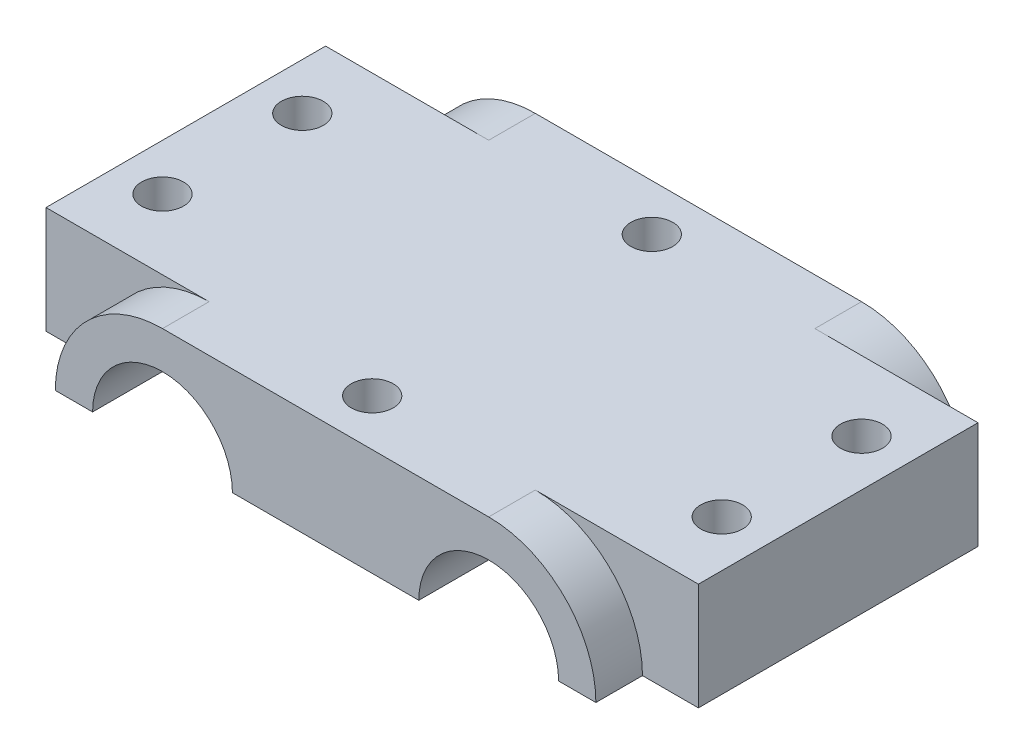
SolidWorks part; units mm, degrees
ref_plane "Front Plane" through (0, 0, 0) normal (0, 0, 1) x (1, 0, 0)
ref_plane "Top Plane" through (0, 0, 0) normal (0, 1, 0) x (1, 0, 0)
ref_plane "Right Plane" through (0, 0, 0) normal (1, 0, 0) x (0, 0, -1)
sketch "Sketch1" plane through (0, 0, 0) normal (0, 0, 1) x (1, 0, 0)
  line L1 (-35, 5.75) -> (35, 5.75)
  line L2 (-35, 5.75) -> (-35, -5.75)
  line L3 (-35, -5.75) -> (35, -5.75)
  line L4 (35, 5.75) -> (35, -5.75)
  line L5 (-35, 5.75) -> (35, -5.75) construction
  line L6 (-35, -5.75) -> (35, 5.75) construction
  point P0 (0, 0)
  dimension "D1" = 11.5
  dimension "D2" = 70
extrude "Boss-Extrude1" add sketch "Sketch1" along normal mid plane 40
sketch "Sketch2" plane through (0, 0, 20) normal (0, 0, 1) x (1, 0, 0)
  line L0 (-35, -5.75) -> (35, -5.75) construction
  line L1 (0, 0) -> (0, 14.1987) construction
  line L2 (-25, -5.75) -> (-10, -5.75)
  line L3 (10, -5.75) -> (25, -5.75)
  arc A0 (-25, -5.75) -> (-10, -5.75) centre (-17.5, -5.75) cw
  arc A1 (10, -5.75) -> (25, -5.75) centre (17.5, -5.75) cw
  dimension "D2" = 7.5
  dimension "D1" = 35
extrude "Cut-Extrude1" cut sketch "Sketch2" against normal through all
sketch "Sketch3" plane through (0, 0, 20) normal (0, 0, 1) x (1, 0, 0)
  line L0 (25, -5.75) -> (35, -5.75) construction
  line L1 (35, 5.75) -> (-35, 5.75) construction
  line L2 (-35, 5.75) -> (-35, -5.75) construction
  line L3 (35, -5.75) -> (35, 5.75) construction
  line L4 (-35, 5.75) -> (-35, -5.75)
  line L5 (35, -5.75) -> (35, 5.75)
  line L6 (35, 5.75) -> (17.5, 5.75)
  line L7 (0, -10.9718) -> (0, 10.9718) construction
  line L8 (-17.5, 5.75) -> (-35, 5.75)
  line L9 (-35, -5.75) -> (-25, -5.75) construction
  line L10 (-35, -5.75) -> (-29, -5.75)
  line L11 (29, -5.75) -> (35, -5.75)
  arc A0 (29, -5.75) -> (17.5, 5.75) centre (17.5, -5.75) ccw
  arc A1 (-29, -5.75) -> (-17.5, 5.75) centre (-17.5, -5.75) cw
  dimension "D1" = 11.5
extrude "Cut-Extrude2" cut sketch "Sketch3" against normal blind 5
mirror "Mirror1" about plane through (0, 0, 0) normal (0, 0, 1) of "Cut-Extrude2"
hole_wizard "Hole1" positions "Sketch4" profile "Sketch5" legacy end condition through all
sketch "Sketch4" plane through (0, 5.75, 0) normal (0, 1, 0) x (1, 0, 0)
  point P0 (30, -7.5)
  point P2 (30, 7.5)
  point P9 (35, -0.9697)
  point P13 (0, 0)
  dimension "D1" = 15
  dimension "D2" = 7.5
  dimension "D3" = 30
sketch "Sketch5" plane through (30, 5.75, 7.5) normal (1, 0, 0) x (0, 0, 1)
  line L0 (0, 0) -> (0, 11.5)
  line L1 (0, 11.5) -> (2.25, 11.5)
  line L2 (2.25, 11.5) -> (2.25, 0)
  line L3 (2.25, 0) -> (0, 0)
  line L4 (0, 110) -> (0, -10) construction
  dimension "Diameter" = 4.5
  dimension "Depth" = 11.5
mirror "Mirror2" about plane through (0, 0, 0) normal (1, 0, 0) of "Hole1"
hole_wizard "Hole2" positions "Sketch6" profile "Sketch7" legacy end condition through all
sketch "Sketch6" plane through (0, 5.75, 0) normal (0, 1, 0) x (1, 0, 0)
  point P0 (0, 15)
  point P2 (0, -15)
  point P6 (0, 0)
  point P7 (0, 0)
  dimension "D1" = 30
  dimension "D2" = 15
sketch "Sketch7" plane through (0, 5.75, -15) normal (1, 0, 0) x (0, 0, 1)
  line L0 (0, 0) -> (0, 11.5)
  line L1 (0, 11.5) -> (2.25, 11.5)
  line L2 (2.25, 11.5) -> (2.25, 0)
  line L3 (2.25, 0) -> (0, 0)
  line L4 (0, 110) -> (0, -10) construction
  dimension "Diameter" = 4.5
  dimension "Depth" = 11.5
